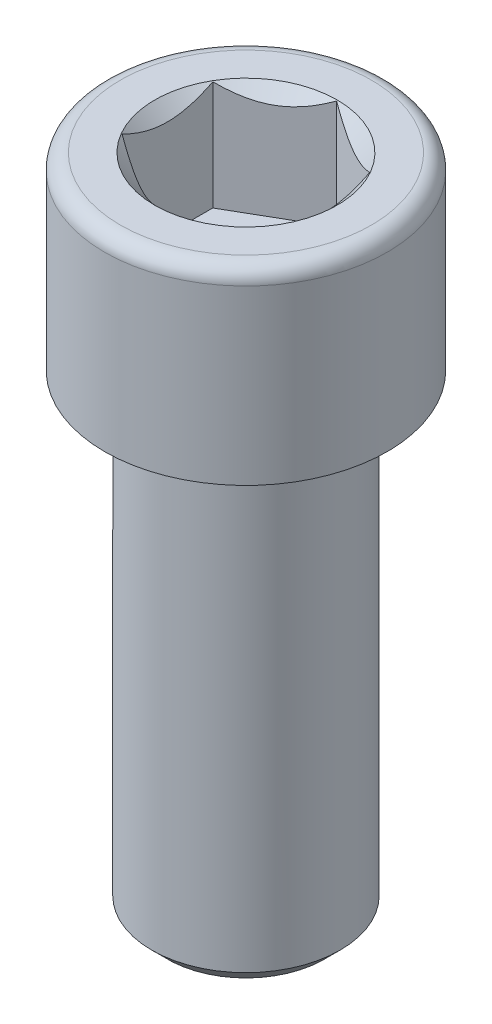
SolidWorks part; units mm, degrees
ref_plane "Przednia" through (0, 0, 0) normal (0, 0, 1) x (1, 0, 0)
ref_plane "Górna" through (0, 0, 0) normal (0, 1, 0) x (1, 0, 0)
ref_plane "Prawa" through (0, 0, 0) normal (1, 0, 0) x (0, 0, -1)
sketch "Szkic1" plane through (0, 0, 0) normal (0, 1, 0) x (1, 0, 0)
  circle A0 centre (0, 0) radius 9
  dimension "D1" = 18
extrude "Wyciągnięcie1" add sketch "Szkic1" along normal blind 12
sketch "Szkic2" plane through (0, 0, 0) normal (0, -1, 0) x (1, 0, 0)
  circle A0 centre (0, 0) radius 6
  dimension "D1" = 12
extrude "Wyciągnięcie2" add sketch "Szkic2" along normal blind 30
cosmetic thread "Oznaczenie gwintu1" parameters "D2"=10.072
sketch "Szkic3" plane through (0, 12, 0) normal (0, 1, 0) x (-1, 0, 0)
  line L1 (0, 5.7735) -> (-5, 2.8868)
  line L2 (-5, 2.8868) -> (-5, -2.8868)
  line L3 (-5, -2.8868) -> (0, -5.7735)
  line L4 (0, -5.7735) -> (5, -2.8868)
  line L5 (5, -2.8868) -> (5, 2.8868)
  line L6 (5, 2.8868) -> (0, 5.7735)
  circle A0 centre (0, 0) radius 5 construction
  dimension "D1" = 10
extrude "Wytnij-wyciągnięcie1" cut sketch "Szkic3" against normal blind 7
sketch "Szkic4" plane through (0, 12, 0) normal (0, 1, 0) x (-1, 0, 0)
  circle A0 centre (0, 0) radius 5.8109
extrude "Wytnij-wyciągnięcie2" cut sketch "Szkic4" against normal blind 2 draft 45
fillet "Zaokrąglenie1" radius 1 1 edges at (0, 12, 9)
chamfer "Sfazowanie1" distance 1 angle 45 1 edges at (0, -30, -6)
